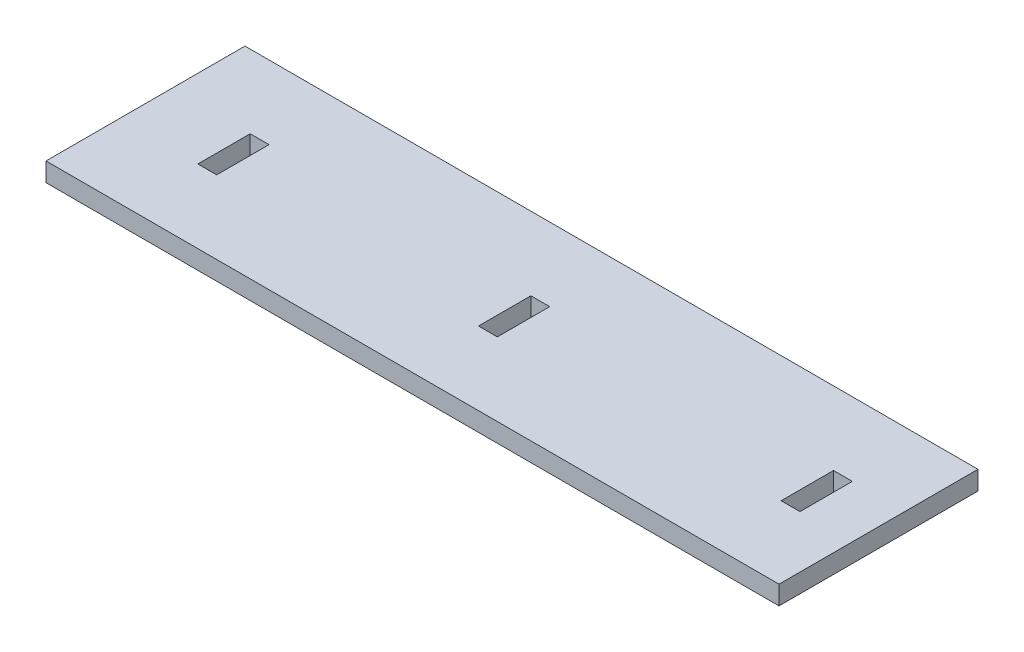
SolidWorks part; units mm, degrees
ref_plane "Front Plane" through (0, 0, 0) normal (0, 0, 1) x (1, 0, 0)
ref_plane "Top Plane" through (0, 0, 0) normal (0, 1, 0) x (1, 0, 0)
ref_plane "Right Plane" through (0, 0, 0) normal (1, 0, 0) x (0, 0, -1)
sketch "Sketch1" plane through (0, 0, 0) normal (0, 1, 0) x (1, 0, 0)
  line L1 (0, 0) -> (177.8, 0)
  line L2 (0, 0) -> (0, 48.26)
  line L3 (0, 48.26) -> (177.8, 48.26)
  line L4 (177.8, 0) -> (177.8, 48.26)
  line L5 (165.1, 17.78) -> (160.528, 17.78)
  line L6 (165.1, 17.78) -> (165.1, 30.48)
  line L7 (165.1, 30.48) -> (160.528, 30.48)
  line L8 (160.528, 17.78) -> (160.528, 30.48)
  line L9 (91.694, 17.78) -> (87.122, 17.78)
  line L10 (91.694, 17.78) -> (91.694, 30.48)
  line L11 (91.694, 30.48) -> (87.122, 30.48)
  line L12 (87.122, 17.78) -> (87.122, 30.48)
  line L13 (23.622, 17.78) -> (19.05, 17.78)
  line L14 (23.622, 17.78) -> (23.622, 30.48)
  line L15 (23.622, 30.48) -> (19.05, 30.48)
  line L16 (19.05, 17.78) -> (19.05, 30.48)
  point P17 (0, 24.13)
  point P18 (19.05, 24.13)
  dimension "D1" = 177.8
  dimension "D2" = 48.26
  dimension "D3" = 19.05
  dimension "D4" = 12.7
  dimension "D5" = 63.5
  dimension "D6" = 4.572
  dimension "D7" = 12.7
extrude "Boss-Extrude1" add sketch "Sketch1" along normal blind 4.572
